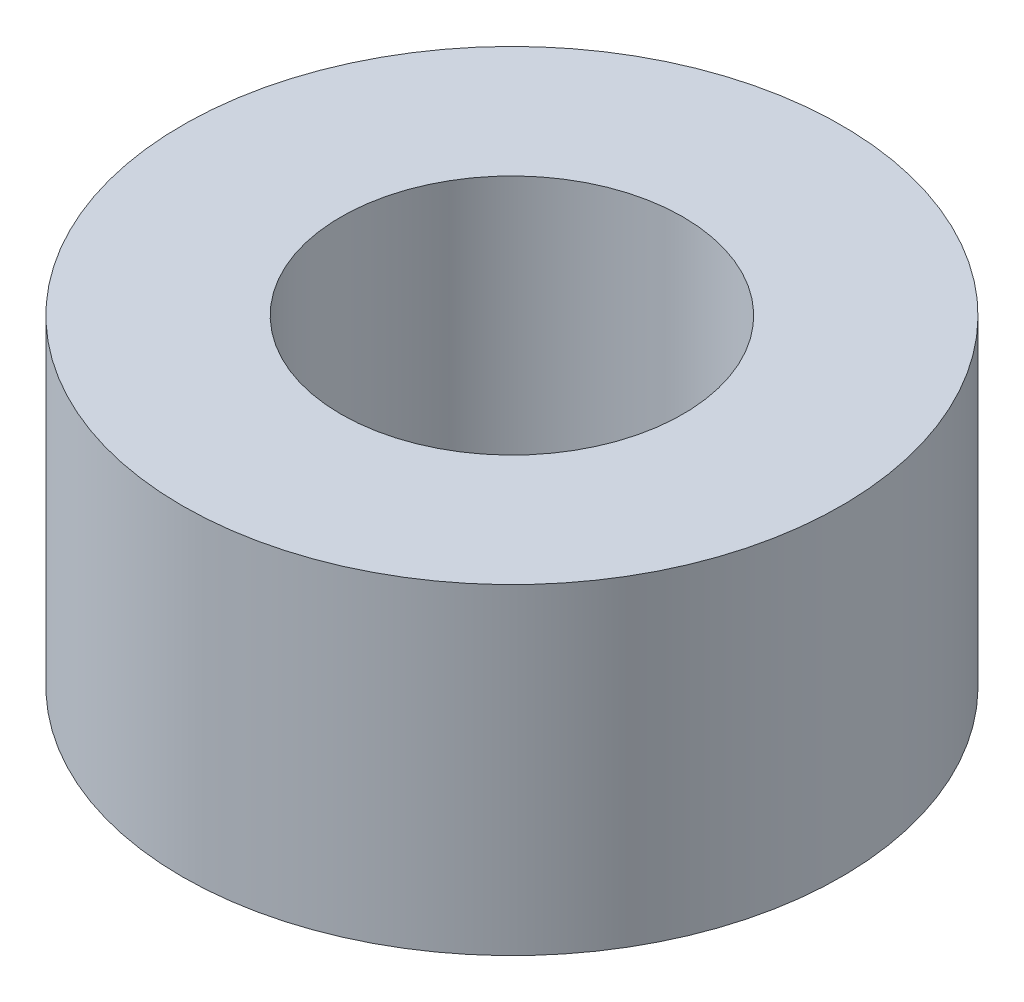
SolidWorks part; units mm, degrees
ref_plane "Ebene vorne" through (0, 0, 0) normal (0, 0, 1) x (1, 0, 0)
ref_plane "Ebene oben" through (0, 0, 0) normal (0, 1, 0) x (1, 0, 0)
ref_plane "Ebene rechts" through (0, 0, 0) normal (1, 0, 0) x (0, 0, -1)
sketch "Skizze2" plane through (0, 0, 0) normal (0, 1, 0) x (1, 0, 0)
  circle A0 centre (0, 0) radius 4
  dimension "D1" = 8
extrude "Aufsatz-Linear austragen1" add sketch "Skizze2" along normal blind 3.9
sketch "Skizze3" plane through (0, 0, 0) normal (0, -1, 0) x (1, 0, 0)
  circle A0 centre (0, 0) radius 2.075
  dimension "D1" = 4.15
extrude "Schnitt-Linear austragen1" cut sketch "Skizze3" against normal blind 3.9
